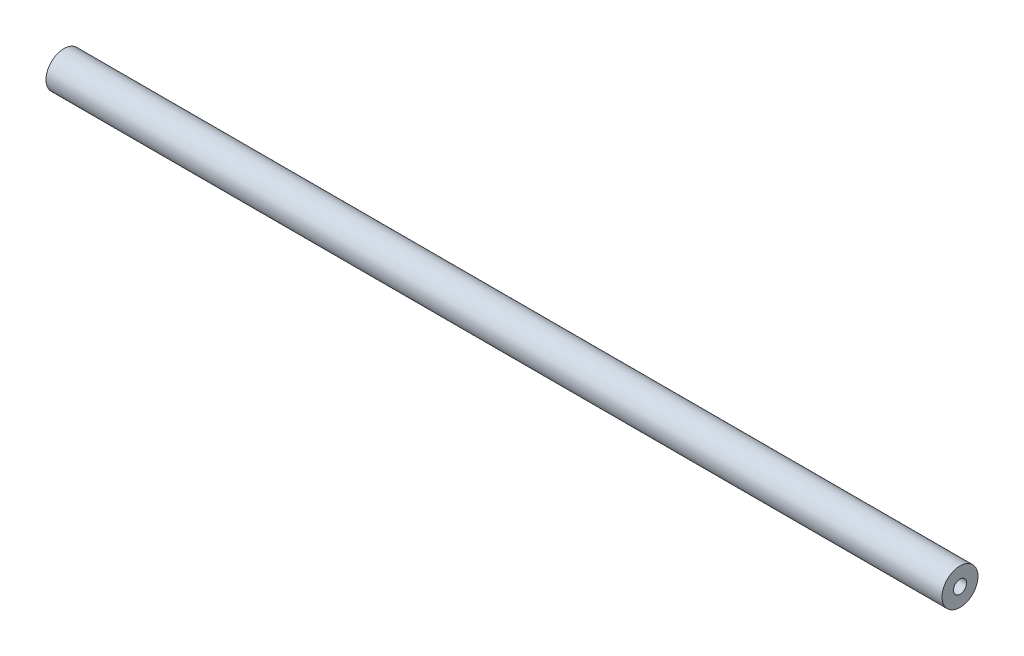
SolidWorks part; units mm, degrees
material "6061-T6 (SS)"
ref_plane "前视基准面" through (0, 0, 0) normal (0, 0, 1) x (1, 0, 0)
ref_plane "上视基准面" through (0, 0, 0) normal (0, 1, 0) x (1, 0, 0)
ref_plane "右视基准面" through (0, 0, 0) normal (1, 0, 0) x (0, 0, -1)
other "Configuration Table"
sketch "草图1" plane through (0, 0, 0) normal (1, 0, 0) x (0, 0, -1)
  circle A0 centre (0, 0) radius 1.65
  circle A1 centre (0, 0) radius 4.5
  dimension "D1" = 3.3
  dimension "D2" = 9
extrude "凸台-拉伸1" add sketch "草图1" along normal blind 224
